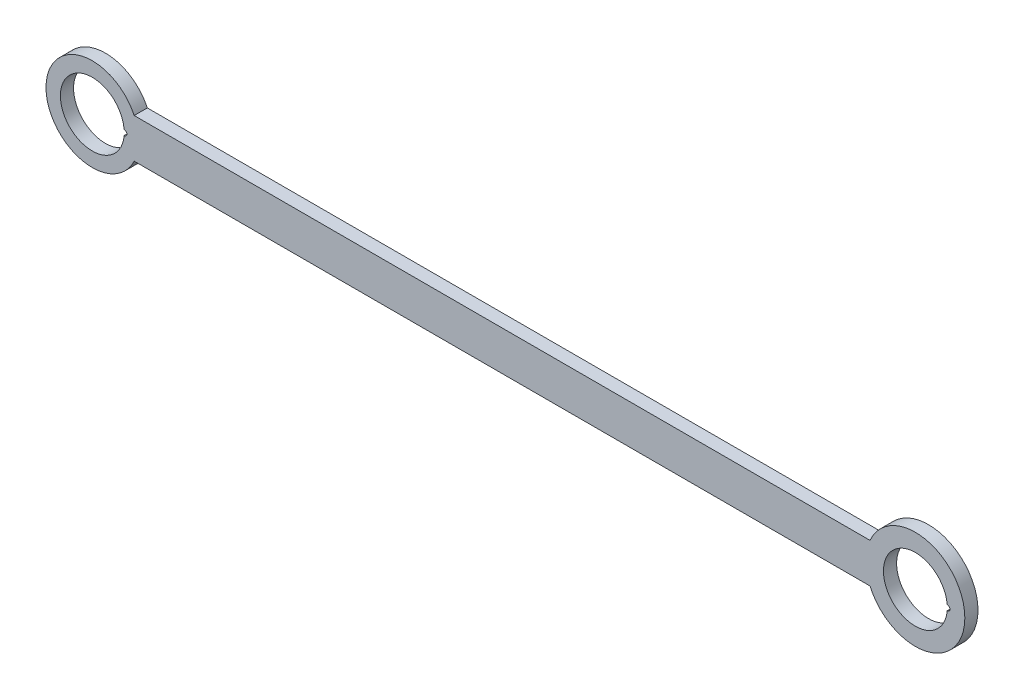
SolidWorks part; units mm, degrees
ref_plane "前视基准面" through (0, 0, 0) normal (0, 0, 1) x (1, 0, 0)
ref_plane "上视基准面" through (0, 0, 0) normal (0, 1, 0) x (1, 0, 0)
ref_plane "右视基准面" through (0, 0, 0) normal (1, 0, 0) x (0, 0, -1)
sketch "草图1" plane through (0, 0, 0) normal (0, 0, 1) x (1, 0, 0)
  line L0 (0, 0) -> (250, 0) construction
  line L1 (12.7187, 6) -> (236.2245, 6)
  line L2 (35.8014, 6) -> (35.8014, 0) construction
  line L3 (12.7187, -6) -> (236.2245, -6)
  line L4 (35.8014, 0) -> (35.8014, -6) construction
  circle A0 centre (0, 0) radius 9.7
  circle A1 centre (250, 0) radius 9.7
  circle A2 centre (0, 0) radius 14.0629 construction
  circle A3 centre (250, 0) radius 15.0255 construction
  arc A4 (12.7187, -6) -> (12.7187, 6) centre (0, 0) cw
  arc A5 (236.2245, -6) -> (236.2245, 6) centre (250, 0) ccw
  dimension "D1" = 19.4
  dimension "D3" = 6
  dimension "D2" = 250
extrude "凸台-拉伸1" add sketch "草图1" along normal blind 4 contours L3 A5 L1 A4
sketch "草图3" plane through (0, 0, 4) normal (0, 0, 1) x (1, 0, 0)
  circle A0 centre (9.7, 0) radius 0.8
  circle A1 centre (0, 0) radius 9.7 construction
  circle A2 centre (259.7, 0) radius 0.8
  circle A3 centre (250, 0) radius 9.7 construction
extrude "切除-拉伸1" cut sketch "草图3" against normal blind 10
